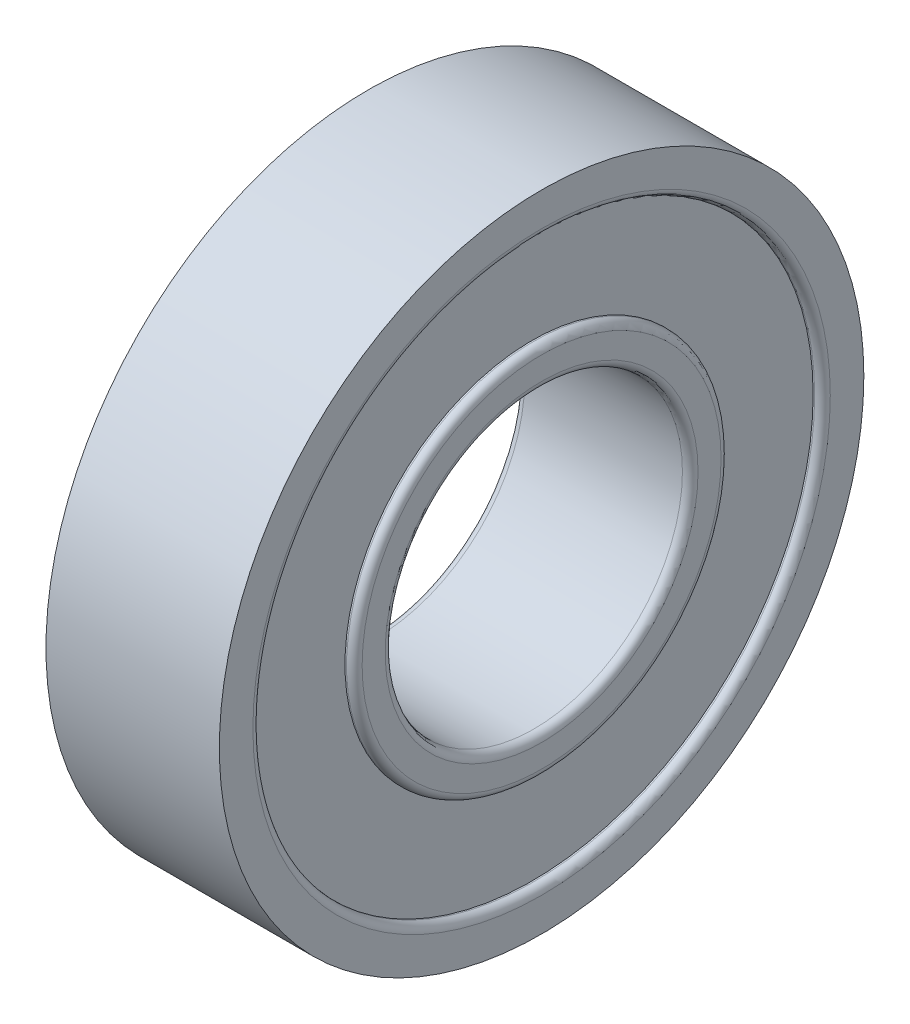
SolidWorks part; units mm, degrees
material "Acero aleado"
ref_plane "Alzado" through (0, 0, 0) normal (0, 0, 1) x (1, 0, 0)
ref_plane "Planta" through (0, 0, 0) normal (0, 1, 0) x (1, 0, 0)
ref_plane "Vista lateral" through (0, 0, 0) normal (1, 0, 0) x (0, 0, -1)
sketch "Croquis1" plane through (0, 0, 0) normal (1, 0, 0) x (0, 0, -1)
  circle A0 centre (0, 0) radius 20.65
  circle A1 centre (0, 0) radius 9.525
  dimension "D1" = 41.3
  dimension "D2" = 19.05
extrude "Saliente-Extruir1" add sketch "Croquis1" along normal mid plane 11.11
sketch "Croquis2" plane through (5.555, 0, 0) normal (1, 0, 0) x (0, 0, -1)
  circle A0 centre (0, 0) radius 18
  circle A1 centre (0, 0) radius 12
  dimension "D1" = 36
  dimension "D2" = 24
extrude "Cortar-Extruir1" cut sketch "Croquis2" against normal blind 0.6
mirror "Simetría2" about plane through (0, 0, 0) normal (1, 0, 0) of "Cortar-Extruir1"
fillet "Redondeo1" radius 0.5 6 edges at (-5.555, 0, -18) (-5.555, 0, -12) (-5.555, 0, -9.525) (5.555, 0, -9.525) (5.555, 0, -12) (5.555, 0, -18)
